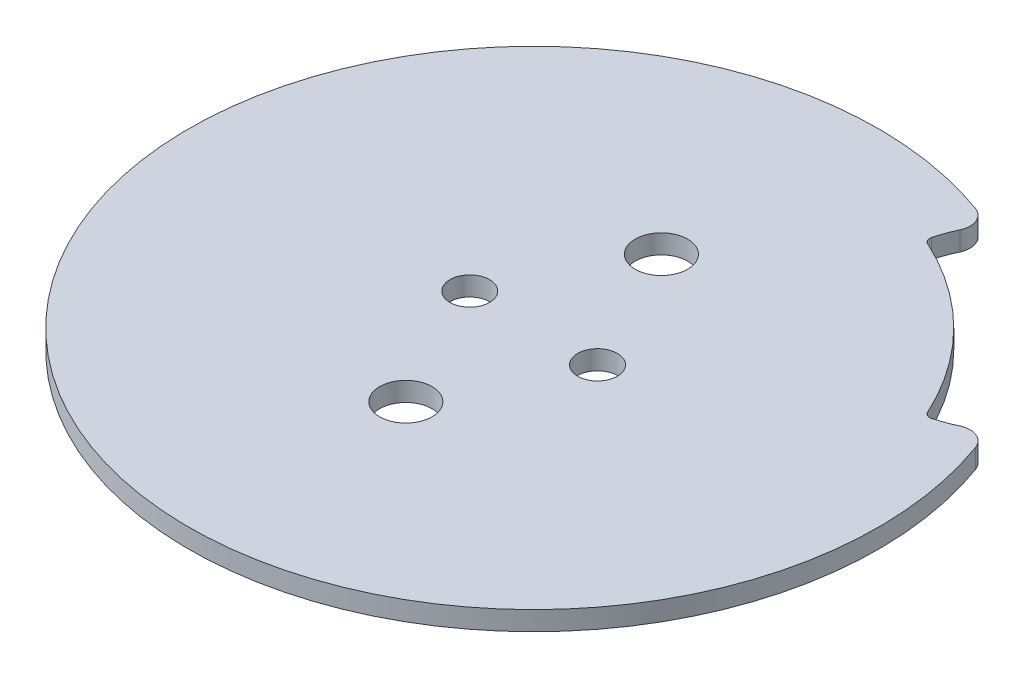
SolidWorks part; units mm, degrees
ref_plane "Front Plane" through (0, 0, 0) normal (0, 0, 1) x (1, 0, 0)
ref_plane "Top Plane" through (0, 0, 0) normal (0, 1, 0) x (1, 0, 0)
ref_plane "Right Plane" through (0, 0, 0) normal (1, 0, 0) x (0, 0, -1)
sketch "Sketch1" plane through (0, 0, 0) normal (0, 1, 0) x (1, 0, 0)
  line L0 (38.1838, 38.1838) -> (0, 0) construction
  line L1 (0, 0) -> (-49.6397, 0) construction
  circle A0 centre (0, 0) radius 54
  circle A1 centre (0, 0) radius 20 construction
  circle A2 centre (0, 20) radius 4.1
  circle A3 centre (0, -20) radius 4.1
  circle A4 centre (-10, 0) radius 3.1
  circle A5 centre (10, 0) radius 3.1
  circle A6 centre (0, 0) radius 10 construction
  circle A7 centre (38.1838, 38.1838) radius 20
  circle A8 centre (0, 0) radius 46.5
  dimension "D1" = 8.2
  dimension "D2" = 40
  dimension "D3" = 108
  dimension "D4" = 20
  dimension "D5" = 6.2
  dimension "D7" = 40
  dimension "D8" = 93
  dimension "D6" = 135
extrude "Boss-Extrude1" add sketch "Sketch1" along normal blind 3 contours A8 A7 A0 | A7 A8 A5 A4 A3 A2 | A7 A8
fillet "Fillet1" radius 3 2 edges at (49.4624, 1.5, -21.6673) (21.6673, 1.5, -49.4624)
fillet "Fillet2" radius 1 2 edges at (18.6742, 1.5, -42.5855) (42.5855, 1.5, -18.6742)
